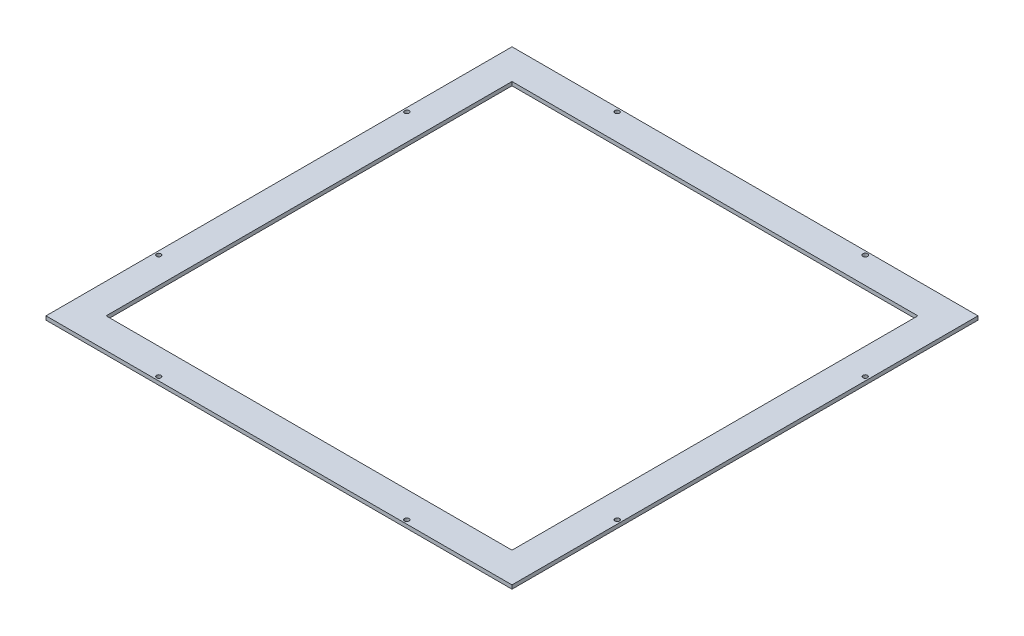
SolidWorks part; units mm, degrees
ref_plane "Front Plane" through (0, 0, 0) normal (0, 0, 1) x (1, 0, 0)
ref_plane "Top Plane" through (0, 0, 0) normal (0, 1, 0) x (1, 0, 0)
ref_plane "Right Plane" through (0, 0, 0) normal (1, 0, 0) x (0, 0, -1)
sketch "Sketch1" plane through (0, 0, 0) normal (0, 1, 0) x (1, 0, 0)
  line L1 (196.85, 196.85) -> (-196.85, 196.85)
  line L2 (196.85, 196.85) -> (196.85, -196.85)
  line L3 (196.85, -196.85) -> (-196.85, -196.85)
  line L4 (-196.85, 196.85) -> (-196.85, -196.85)
  line L5 (196.85, 196.85) -> (-196.85, -196.85) construction
  line L6 (196.85, -196.85) -> (-196.85, 196.85) construction
  point P0 (0, 0)
extrude "Boss-Extrude1" add sketch "Sketch1" along normal blind 3.175
sketch "Sketch2" plane through (0, 3.175, 0) normal (0, 1, 0) x (1, 0, 0)
  line L1 (171.45, 171.45) -> (-171.45, 171.45)
  line L2 (171.45, 171.45) -> (171.45, -171.45)
  line L3 (171.45, -171.45) -> (-171.45, -171.45)
  line L4 (-171.45, 171.45) -> (-171.45, -171.45)
  line L5 (171.45, 171.45) -> (-171.45, -171.45) construction
  line L6 (171.45, -171.45) -> (-171.45, 171.45) construction
  point P0 (0, 0)
extrude "Cut-Extrude1" cut sketch "Sketch2" against normal through all
sketch "Sketch3" plane through (0, 3.175, 0) normal (0, 1, 0) x (1, 0, 0)
  line L0 (-196.85, 196.85) -> (-196.85, -196.85) construction
  line L1 (196.85, -196.85) -> (196.85, 196.85) construction
  line L2 (-196.85, -196.85) -> (196.85, -196.85) construction
  line L4 (196.85, 196.85) -> (-196.85, 196.85) construction
  circle A0 centre (-104.775, -193.675) radius 1.905
  circle A1 centre (104.775, -193.675) radius 1.905
  circle A2 centre (-193.675, -104.775) radius 1.905
  circle A3 centre (-193.675, 104.775) radius 1.905
  circle A4 centre (-104.775, 193.675) radius 1.905
  circle A5 centre (104.775, 193.675) radius 2.0197
  circle A6 centre (193.675, 104.775) radius 1.905
  circle A7 centre (193.675, -104.775) radius 1.905
  point P22 (0, 0)
  point P25 (0, 0)
  point P26 (0, 0)
  dimension "D1" = 92.075
  dimension "D4" = 3.175
  dimension "D2" = 209.55
  dimension "D3" = 92.075
  dimension "D7" = 92.075
  dimension "D8" = 209.55
  dimension "D13" = 92.075
  dimension "D16" = 209.55
  dimension "D22" = 209.55
extrude "Cut-Extrude2" cut sketch "Sketch3" against normal through all
